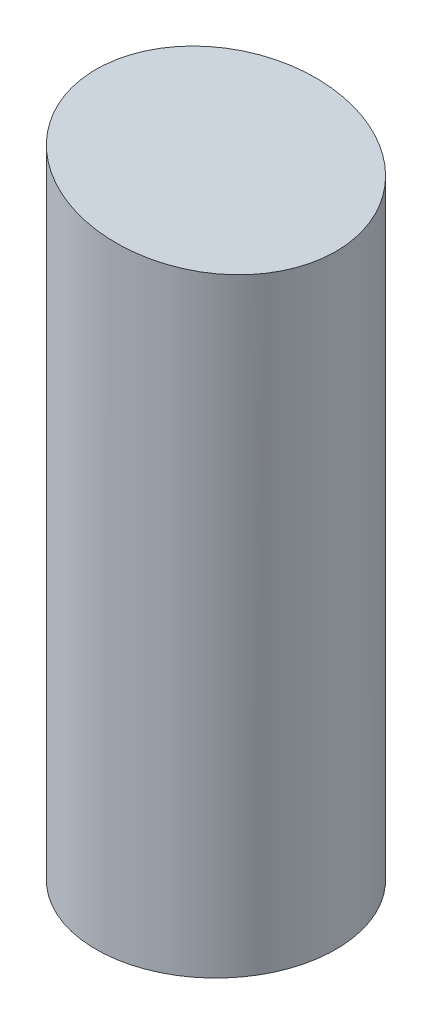
SolidWorks part; units mm, degrees
ref_plane "Alzado" through (0, 0, 0) normal (0, 0, 1) x (1, 0, 0)
ref_plane "Planta" through (0, 0, 0) normal (0, 1, 0) x (1, 0, 0)
ref_plane "Vista lateral" through (0, 0, 0) normal (1, 0, 0) x (0, 0, -1)
sketch "Croquis1" plane through (0, 0, 0) normal (0, 1, 0) x (1, 0, 0)
  circle A0 centre (0, 0) radius 31.75
  dimension "D1" = 63.5
extrude "Saliente-Extruir1" add sketch "Croquis1" along normal blind 170
sketch "Croquis2" plane through (0, 0, 0) normal (0, 0, 1) x (1, 0, 0)
  line L0 (-31.75, 170) -> (31.75, 160)
  line L1 (31.75, 0) -> (31.75, 170) construction
  line L2 (31.75, 160) -> (31.75, 170)
  line L3 (31.75, 170) -> (-31.75, 170)
  dimension "D1" = 10
extrude "Cortar-Extruir1" cut sketch "Croquis2" against normal mid plane 180
sketch "Croquis3" plane through (0, 0, 0) normal (0, -1, 0) x (1, 0, 0)
  line L0 (-31.75, 0) -> (-31.75, 2)
  line L1 (-31.75, 2) -> (-28.75, 2)
  line L2 (-28.75, 2) -> (-28.75, -2)
  line L3 (-28.75, -2) -> (-31.75, -2)
  line L4 (-31.75, -2) -> (-31.75, 0)
  circle A0 centre (0, 0) radius 31.75 construction
  dimension "D1" = 2
  dimension "D2" = 2
  dimension "D3" = 3
extrude "Saliente-Extruir2" add sketch "Croquis3" against normal blind 8
